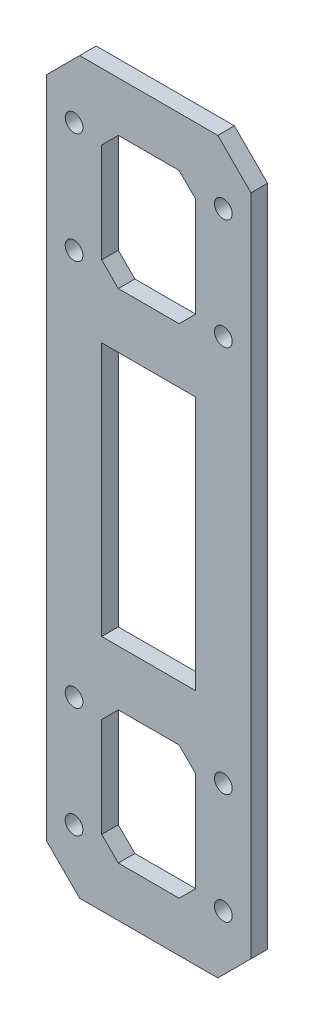
SolidWorks part; units mm, degrees
ref_plane "正面" through (0, 0, 0) normal (0, 0, 1) x (1, 0, 0)
ref_plane "平面" through (0, 0, 0) normal (0, 1, 0) x (1, 0, 0)
ref_plane "右側面" through (0, 0, 0) normal (1, 0, 0) x (0, 0, -1)
sketch "ｽｹｯﾁ1" plane through (0, 0, 0) normal (0, 0, 1) x (1, 0, 0)
  line L1 (0, 0) -> (37, 0)
  line L2 (0, 0) -> (0, 120)
  line L3 (0, 120) -> (37, 120)
  line L4 (37, 0) -> (37, 120)
  circle A0 centre (5, 115) radius 1.6
  circle A1 centre (32, 115) radius 1.6
  circle A2 centre (5, 95) radius 1.6
  circle A3 centre (32, 95) radius 1.6
  circle A4 centre (5, 25) radius 1.6
  circle A5 centre (32, 25) radius 1.6
  circle A6 centre (5, 5) radius 1.6
  circle A7 centre (32, 5) radius 1.6
  dimension "D3" = 5
  dimension "D4" = 3.2
  dimension "D5" = 5
  dimension "D6" = 20
  dimension "D7" = 5
  dimension "D8" = 3.2
  dimension "D9" = 3.2
  dimension "D10" = 5
  dimension "D11" = 20
  dimension "D13" = 5
  dimension "D14" = 3.2
  dimension "D15" = 3.2
  dimension "D16" = 5
  dimension "D17" = 5
  dimension "D18" = 5
  dimension "D19" = 3.2
  dimension "D20" = 5
  dimension "D21" = 5
  dimension "D22" = 20
  dimension "D23" = 3.2
  dimension "D24" = 5
  dimension "D25" = 3.2
  dimension "D26" = 5
  dimension "D27" = 20
  dimension "D1" = 120
  dimension "D2" = 37
  dimension "D12" = 5
extrude "ﾎﾞｽ - 押し出し1" add sketch "ｽｹｯﾁ1" along normal blind 3
sketch "ｽｹｯﾁ2" plane through (0, 0, 3) normal (0, 0, 1) x (1, 0, 0)
  line L0 (0, 120) -> (0, 0) construction
  line L1 (10, 117) -> (27, 117)
  line L2 (10, 117) -> (10, 93)
  line L3 (10, 93) -> (27, 93)
  line L4 (27, 117) -> (27, 93)
  line L5 (10, 27) -> (27, 27)
  line L6 (10, 27) -> (10, 3)
  line L7 (10, 3) -> (27, 3)
  line L8 (27, 27) -> (27, 3)
  line L9 (37, 0) -> (37, 120) construction
  line L10 (37, 120) -> (0, 120) construction
  line L11 (0, 0) -> (37, 0) construction
  point P12 (10, 105)
  point P15 (10, 15)
  dimension "D1" = 10
  dimension "D2" = 10
  dimension "D3" = 24
  dimension "D4" = 15
  dimension "D5" = 15
  dimension "D6" = 10
  dimension "D7" = 10
  dimension "D8" = 24
extrude "ｶｯﾄ - 押し出し1" cut sketch "ｽｹｯﾁ2" against normal through all
sketch "ｽｹｯﾁ3" plane through (0, 0, 3) normal (0, 0, 1) x (1, 0, 0)
  line L0 (37, 0) -> (37, 120) construction
  line L1 (0, 120) -> (37, 120)
  line L2 (0, 120) -> (0, 126)
  line L3 (0, 126) -> (37, 126)
  line L4 (37, 120) -> (37, 126)
  line L5 (0, 0) -> (37, 0)
  line L6 (0, 0) -> (0, -6)
  line L7 (0, -6) -> (37, -6)
  line L8 (37, 0) -> (37, -6)
  dimension "D1" = 0
  dimension "D2" = 0
  dimension "D3" = 6
  dimension "D4" = 6
extrude "ﾎﾞｽ - 押し出し2" add sketch "ｽｹｯﾁ3" against normal blind 3
chamfer "面取り1" distance 6 angle 45 4 edges at (37, 126, 1.5) (0, 126, 1.5) (37, -6, 1.5) (0, -6, 1.5)
chamfer "面取り2" distance 3 angle 45 8 edges at (10, 3, 1.5) (27, 3, 1.5) (27, 27, 1.5) (10, 27, 1.5) (27, 93, 1.5) (10, 93, 1.5) (10, 117, 1.5) (27, 117, 1.5)
sketch "ｽｹｯﾁ4" plane through (0, 0, 3) normal (0, 0, 1) x (1, 0, 0)
  line L0 (13, 93) -> (24, 93) construction
  line L1 (10, 83) -> (27, 83)
  line L2 (10, 83) -> (10, 37)
  line L3 (10, 37) -> (27, 37)
  line L4 (27, 83) -> (27, 37)
  line L5 (24, 27) -> (13, 27) construction
  line L6 (37, 0) -> (37, 120) construction
  line L7 (0, 120) -> (0, 0) construction
  dimension "D1" = 10
  dimension "D2" = 10
  dimension "D3" = 10
  dimension "D4" = 10
extrude "ｶｯﾄ - 押し出し2" cut sketch "ｽｹｯﾁ4" against normal blind 10
